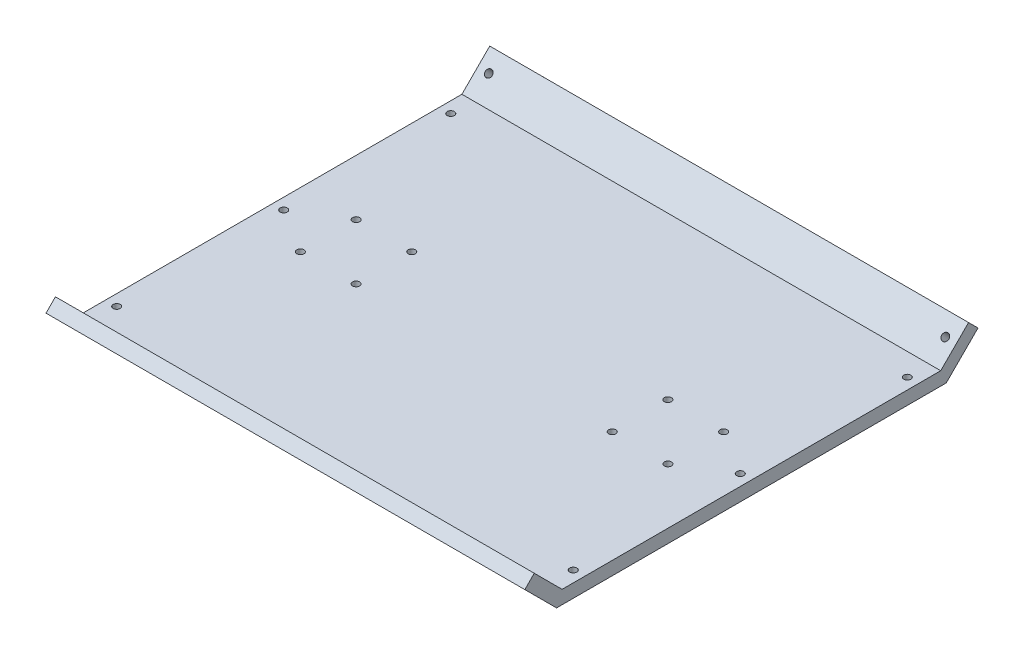
SolidWorks part; units mm, degrees
ref_plane "Front Plane" through (0, 0, 0) normal (0, 0, 1) x (1, 0, 0)
ref_plane "Top Plane" through (0, 0, 0) normal (0, 1, 0) x (1, 0, 0)
ref_plane "Right Plane" through (0, 0, 0) normal (1, 0, 0) x (0, 0, -1)
sketch "Sketch2" plane through (0, 0, 0) normal (1, 0, 0) x (0, 0, -1)
  line L0 (-85, 0) -> (85, 0)
  line L1 (85, 0) -> (97.5, 12.5)
  line L2 (-85, 0) -> (-97.5, 12.5)
  line L8 (-87.4853, -6) -> (-101.7426, 8.2574)
  line L9 (-87.4853, -6) -> (87.4853, -6)
  line L10 (87.4853, -6) -> (101.7426, 8.2574)
  line L11 (-101.7426, 8.2574) -> (-97.5, 12.5)
  line L12 (97.5, 12.5) -> (101.7426, 8.2574)
  line L13 (97.5, 12.5) -> (110, 25) construction
  line L14 (-97.5, 12.5) -> (-110, 25) construction
  point P4 (0, 0)
  dimension "D2" = 135
  dimension "D3" = 135
  dimension "D1" = 220
  dimension "D4" = 25
  dimension "D5" = 6
extrude "Main" add sketch "Sketch2" along normal mid plane 215
hole_wizard "Ø3.0mm Dowel Hole1" positions "3DSketch1" profile "Sketch3" hole size "Ø4.0" standard "ANSI Metric" end condition through all
sketch3d "3DSketch1"
  line L0 (-107.5, 7.0711, -92.0711) -> (-102.5, 7.0711, -92.0711) construction
  line L1 (-107.5, 12.5, -97.5) -> (-107.5, 0, -85) construction
  line L2 (-102.5, 7.0711, -92.0711) -> (-102.5, 0, -85) construction
  line L3 (107.5, 0, -85) -> (-107.5, 0, -85) construction
  line L4 (-102.5, 0, -85) -> (-102.5, 0, -75) construction
  line L5 (-102.5, 0, -75) -> (-102.5, 0, 0) construction
  line L6 (-102.5, 0, 0) -> (-102.5, 0, 75) construction
  line L7 (-102.5, 0, 75) -> (-102.5, 0, 85) construction
  line L8 (107.5, 0, 85) -> (-107.5, 0, 85) construction
  line L13 (-102.5, 0, 85) -> (-102.5, 7.0711, 92.0711) construction
  line L14 (-102.5, 7.0711, 92.0711) -> (-107.5, 7.0711, 92.0711) construction
  line L15 (-107.5, 0, 85) -> (-107.5, 12.5, 97.5) construction
  line L20 (102.5, 0, -85) -> (102.5, 0, -75) construction
  line L21 (102.5, 0, -75) -> (102.5, 0, 0) construction
  line L22 (102.5, 0, 0) -> (102.5, 0, 75) construction
  line L23 (102.5, 0, 75) -> (102.5, 0, 85) construction
  line L24 (102.5, 0, 85) -> (102.5, 7.0711, 92.0711) construction
  line L25 (102.5, 7.0711, 92.0711) -> (107.5, 7.0711, 92.0711) construction
  line L26 (107.5, 0, 85) -> (107.5, 12.5, 97.5) construction
  line L28 (102.5, 0, -85) -> (102.5, 7.0711, -92.0711) construction
  line L29 (102.5, 7.0711, -92.0711) -> (107.5, 7.0711, -92.0711) construction
  line L30 (107.5, 12.5, -97.5) -> (107.5, 0, -85) construction
  line L32 (107.5, 0, 85) -> (102.5, 0, 85) construction
  line L34 (-102.5, 0, 85) -> (-107.5, 0, 85) construction
  point P0 (-102.5, 7.0711, -92.0711)
  point P2 (-102.5, 0, -75)
  point P4 (-102.5, 0, 0)
  point P6 (-102.5, 0, 75)
  point P8 (-102.5, 7.0711, 92.0711)
  point P10 (102.5, 7.0711, 92.0711)
  point P12 (102.5, 0, 75)
  point P14 (102.5, 0, 0)
  point P16 (102.5, 0, -75)
  point P18 (102.5, 7.0711, -92.0711)
  dimension "D1" = 5
  dimension "D2" = 10
  dimension "D3" = 10
sketch "Sketch3" plane through (-102.5, 7.0711, -92.0711) normal (1, 0, 0) x (0, -0.7071, 0.7071)
  line L0 (0, 0) -> (0, 16.0815)
  line L1 (0, 16.0815) -> (1.6, 16.0815)
  line L2 (1.6, 16.0815) -> (1.6, 0)
  line L5 (1.6, 0) -> (0, 0)
  line L11 (0, -6.35) -> (0, 107.95) construction
  dimension "Thru Hole Dia." = 3.2
  dimension "Thru Hole Depth" = 16.0815
sketch "Sketch4" plane through (0, -6, 0) normal (0, -1, 0) x (1, 0, 0)
  line L1 (57.5, 12.5) -> (82.5, 12.5) construction
  line L2 (57.5, 12.5) -> (57.5, -12.5) construction
  line L3 (57.5, -12.5) -> (82.5, -12.5) construction
  line L4 (82.5, 12.5) -> (82.5, -12.5) construction
  line L5 (57.5, 12.5) -> (82.5, -12.5) construction
  line L6 (57.5, -12.5) -> (82.5, 12.5) construction
  circle A0 centre (57.5, 12.5) radius 1.6
  circle A1 centre (82.5, 12.5) radius 1.6
  circle A2 centre (82.5, -12.5) radius 1.6
  circle A3 centre (57.5, -12.5) radius 1.6
  point P0 (70, 0)
  dimension "D1" = 3.2
  dimension "D2" = 25
  dimension "D3" = 25
  dimension "D4" = 70
extrude "Attachment screw holes" cut sketch "Sketch4" against normal through all
mirror "Mirror1" about plane through (0, 0, 0) normal (1, 0, 0) of "Attachment screw holes"
equation "\"length\" = 215mm"
equation "\"D1@Main\" = \"length\""
equation "\"width\" = 220mm"
equation "\"height\" = 100mm"
equation "\"skin_th\" = 6mm"
equation "\"D1@Sketch2\"=\"width\""
equation "\"D5@Sketch2\"=\"skin_th\""
